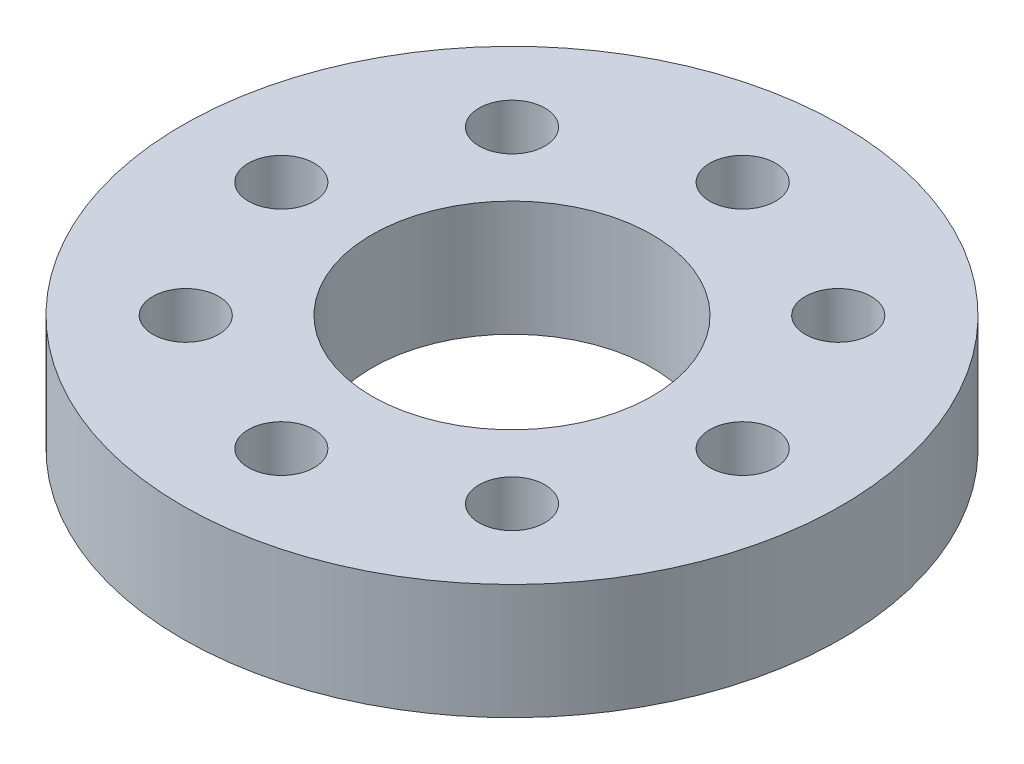
SolidWorks part; units mm, degrees
ref_plane "Front Plane" through (0, 0, 0) normal (0, 0, 1) x (1, 0, 0)
ref_plane "Top Plane" through (0, 0, 0) normal (0, 1, 0) x (1, 0, 0)
ref_plane "Right Plane" through (0, 0, 0) normal (1, 0, 0) x (0, 0, -1)
sketch "Sketch2" plane through (0, 0, 0) normal (0, 1, 0) x (1, 0, 0)
  line L0 (-10.9846, 0) -> (11.4312, 0) construction
  line L1 (0, 4.5811) -> (0, -5.6811) construction
  circle A0 centre (0, 0) radius 10
  circle A1 centre (0, 0) radius 4.25
  circle A2 centre (0, 7) radius 1
  circle A3 centre (4.9497, 4.9497) radius 1
  circle A4 centre (7, 0) radius 1
  circle A5 centre (4.9497, -4.9497) radius 1
  circle A6 centre (0, -7) radius 1
  circle A7 centre (-4.9497, -4.9497) radius 1
  circle A8 centre (-7, 0) radius 1
  circle A9 centre (-4.9497, 4.9497) radius 1
  point P27 (0, 0)
  dimension "D1" = 20
  dimension "D2" = 8.5
  dimension "D4" = 2
  dimension "D3" = 7
  dimension "D5" = 8
extrude "Boss-Extrude1" add sketch "Sketch2" along normal blind 3.5
